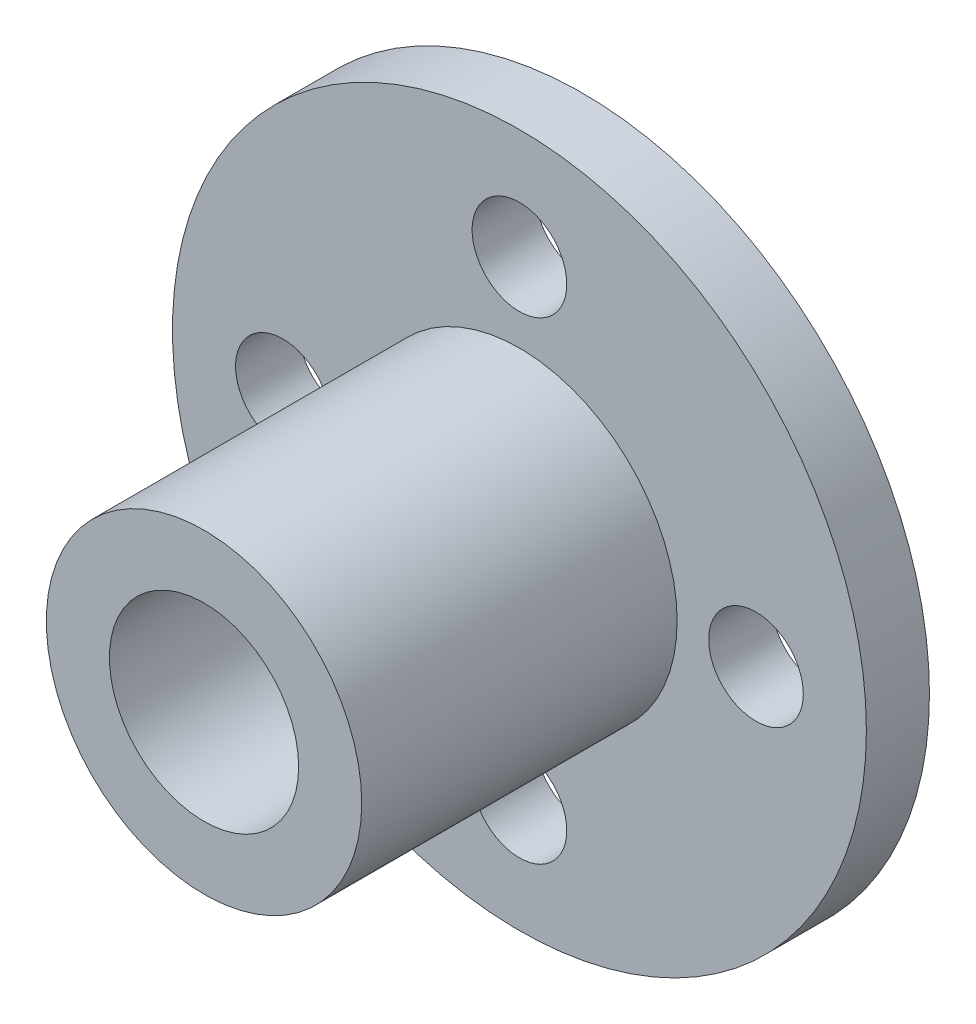
SolidWorks part; units mm, degrees
ref_plane "Front Plane" through (0, 0, 0) normal (0, 0, 1) x (1, 0, 0)
ref_plane "Top Plane" through (0, 0, 0) normal (0, 1, 0) x (1, 0, 0)
ref_plane "Right Plane" through (0, 0, 0) normal (1, 0, 0) x (0, 0, -1)
sketch "Sketch1" plane through (0, 0, 0) normal (0, 0, 1) x (1, 0, 0)
  circle A0 centre (0, 0) radius 11
  dimension "D1" = 22
extrude "Boss-Extrude1" add sketch "Sketch1" along normal blind 2
sketch "Sketch2" plane through (0, 0, 2) normal (0, 0, 1) x (1, 0, 0)
  circle A0 centre (0, 0) radius 5
  dimension "D1" = 10
extrude "Boss-Extrude2" add sketch "Sketch2" along normal blind 10
sketch "Sketch3" plane through (0, 0, 12) normal (0, 0, 1) x (1, 0, 0)
  circle A0 centre (0, 0) radius 3
  dimension "D1" = 6
extrude "Cut-Extrude1" cut sketch "Sketch3" against normal blind 20
sketch "Sketch4" plane through (0, 0, 2) normal (0, 0, 1) x (1, 0, 0)
  line L0 (0, -6.6) -> (0, 6.6) construction
  circle A0 centre (0, 7.5) radius 1.5
  circle A1 centre (0, 0) radius 11 construction
  circle A4 centre (7.5, 0) radius 1.5
  circle A5 centre (0, -7.5) radius 1.5
  circle A6 centre (-7.5, 0) radius 1.5
  point P15 (0, 0)
  dimension "D1" = 3
  dimension "D2" = 7.5
  dimension "D3" = 4
extrude "Cut-Extrude2" cut sketch "Sketch4" against normal blind 20
